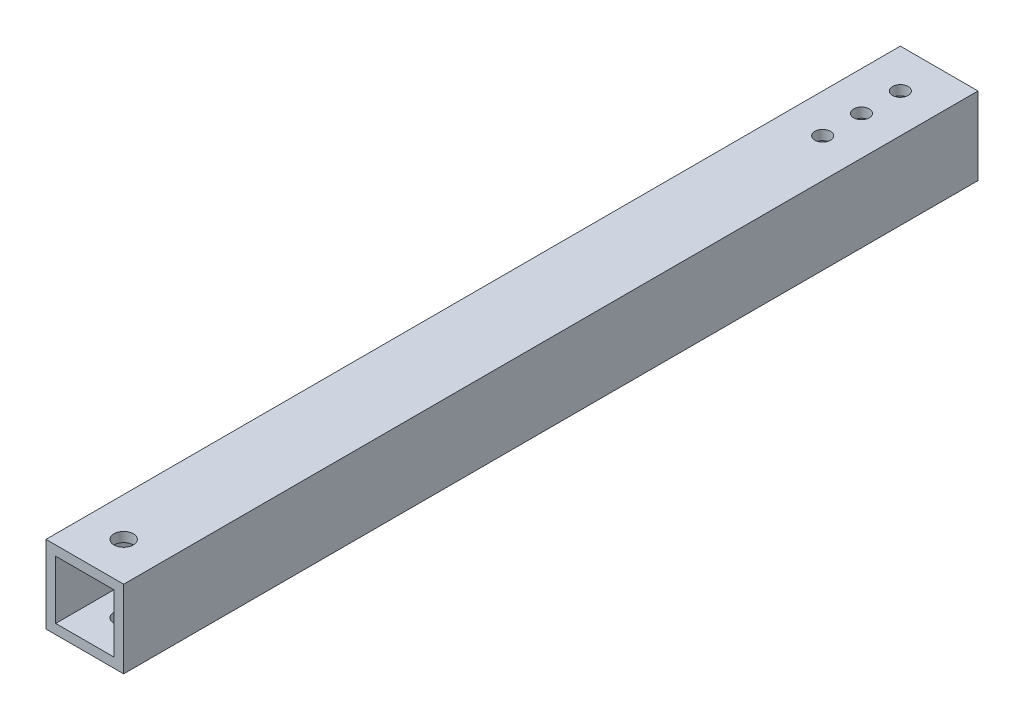
SolidWorks part; units mm, degrees
material "6061 Alloy"
ref_plane "Front" through (0, 0, 0) normal (0, 0, 1) x (1, 0, 0)
ref_plane "Top" through (0, 0, 0) normal (0, 1, 0) x (1, 0, 0)
ref_plane "Right" through (0, 0, 0) normal (1, 0, 0) x (0, 0, -1)
sketch "Sketch1" plane through (0, 0, 0) normal (0, 0, 1) x (1, 0, 0)
  line L1 (0, 0) -> (-25.4, 0)
  line L2 (0, 0) -> (0, 25.4)
  line L3 (0, 25.4) -> (-25.4, 25.4)
  line L4 (-25.4, 0) -> (-25.4, 25.4)
  line L5 (-3.175, 3.175) -> (-22.225, 3.175)
  line L6 (-3.175, 3.175) -> (-3.175, 22.225)
  line L7 (-3.175, 22.225) -> (-22.225, 22.225)
  line L8 (-22.225, 3.175) -> (-22.225, 22.225)
  dimension "D1" = 25.4
  dimension "D2" = 3.175
  dimension "D3" = 3.175
  dimension "D4" = 3.175
  dimension "D5" = 3.175
extrude "Boss-Extrude1" add sketch "Sketch1" along normal blind 279.4
sketch "Sketch2" plane through (0, 0, 0) normal (0, -1, 0) x (-1, 0, 0)
  line L0 (25.4, -279.4) -> (25.4, 0) construction
  line L1 (25.4, -279.4) -> (0, -279.4) construction
  circle A0 centre (12.7, -266.7) radius 3.175
  dimension "D1" = 6.35
  dimension "D2" = 12.7
  dimension "D3" = 12.7
extrude "Cut-Extrude1" cut sketch "Sketch2" against normal through all and the other way through all
hole_wizard "#10 Clearance Hole1" positions "Sketch3" profile "Sketch4" hole size "#10" standard "ANSI Inch"
sketch "Sketch3" plane through (0, 25.4, 0) normal (0, 1, 0) x (1, 0, 0)
  line L1 (0, 0) -> (-25.4, 0) construction
  line L2 (0, -279.4) -> (0, 0) construction
  point P0 (-12.7, -38.1)
  point P2 (-12.7, -25.4)
  point P4 (-12.7, -12.7)
  dimension "D1" = 12.7
  dimension "D2" = 12.7
  dimension "D3" = 12.7
  dimension "D4" = 12.7
sketch "Sketch4" plane through (-12.7, 25.4, 38.1) normal (1, 0, 0) x (0, 0, 1)
  line L0 (0, 0) -> (0, 26.9328)
  line L1 (0, 26.9328) -> (2.5527, 25.399)
  line L2 (2.5527, 25.399) -> (2.5527, 0)
  line L5 (2.5527, 0) -> (0, 0)
  line L10 (0, 26.9328) -> (-2.5527, 25.399) construction
  line L11 (0, -6.35) -> (0, 107.95) construction
  dimension "Hole Dia." = 5.1054
  dimension "Hole Depth" = 25.399
  dimension "Drill Angle" = 118
